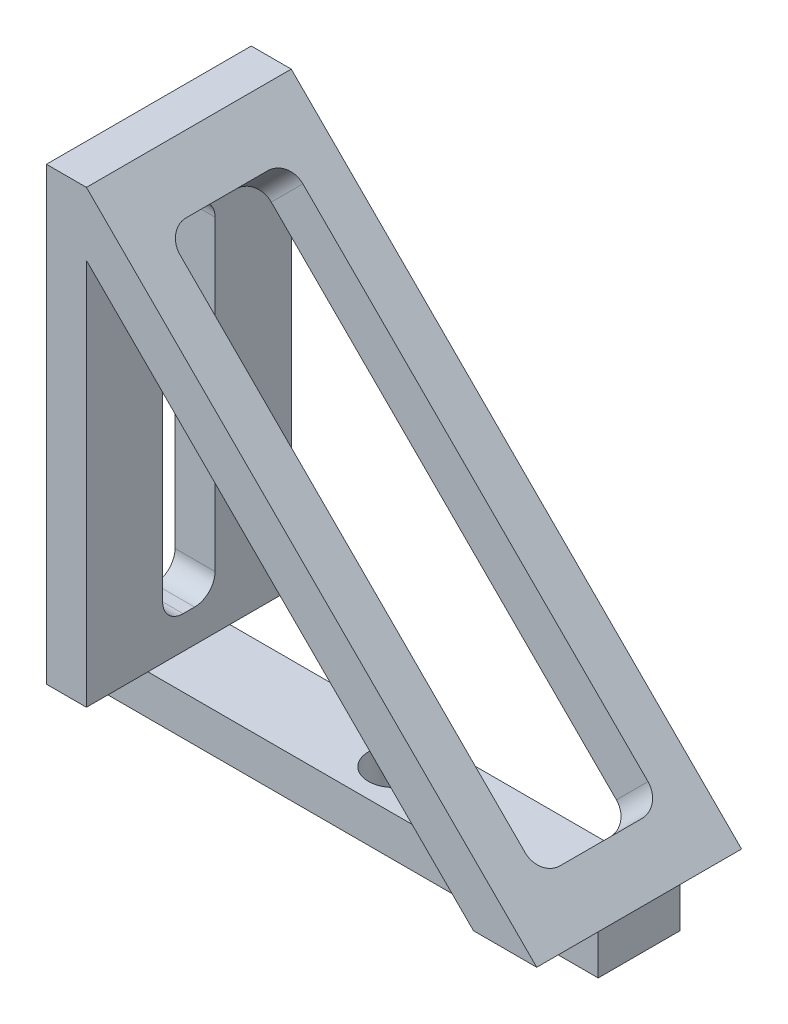
SolidWorks part; units mm, degrees
ref_plane "Front" through (0, 0, 0) normal (0, 0, 1) x (1, 0, 0)
ref_plane "Top" through (0, 0, 0) normal (0, 1, 0) x (1, 0, 0)
ref_plane "Right" through (0, 0, 0) normal (1, 0, 0) x (0, 0, -1)
sketch "Sketch1" plane through (0, 0, 0) normal (0, 0, 1) x (1, 0, 0)
  line L3 (-6.2, 69.8) -> (-6.2, -6.2)
  line L4 (-6.2, -6.2) -> (69.8, -6.2)
  line L6 (-6.2, 69.8) -> (0, 69.8)
  line L7 (0, 69.8) -> (69.8, 0)
  line L8 (50, 0) -> (-50, 0) construction
  line L9 (69.8, 0) -> (69.8, -6.2)
  line L10 (0, 60) -> (60, 0)
  line L11 (60, 0) -> (0, 0)
  line L12 (0, 0) -> (0, 60)
  dimension "D1" = 76
  dimension "D2" = 76
  dimension "D3" = 6.2
  dimension "D4" = 6.2
  dimension "D5" = 60
extrude "Boss-Extrude1" add sketch "Sketch1" along normal mid plane 31.75
sketch "Sketch2" plane through (34.9, 34.9, 0) normal (0.7071, 0.7071, 0) x (0, 0, -1)
  line L0 (0, 50) -> (0, -50) construction
  line L1 (-9.525, -41) -> (9.525, -41)
  line L2 (-9.525, -41) -> (-9.525, 41)
  line L3 (-9.525, 41) -> (9.525, 41)
  line L4 (9.525, -41) -> (9.525, 41)
  line L5 (-9.525, -41) -> (9.525, 41) construction
  line L6 (-9.525, 41) -> (9.525, -41) construction
  point P0 (0, 0)
  point P5 (9.525, 0)
  point P9 (0, 41)
  dimension "D1" = 82
  dimension "D2" = 19.05
extrude "Cut-Extrude1" cut sketch "Sketch2" against normal up to next
sketch "Sketch3" plane through (0, 0, 0) normal (1, 0, 0) x (0, 0, -1)
  line L0 (0, 50) -> (0, -50) construction
  line L1 (-4.064, 5.08) -> (4.064, 5.08)
  line L2 (-4.064, 5.08) -> (-4.064, 59)
  line L3 (-4.064, 59) -> (4.064, 59)
  line L4 (4.064, 5.08) -> (4.064, 59)
  line L5 (-4.064, 5.08) -> (4.064, 59) construction
  line L6 (-4.064, 59) -> (4.064, 5.08) construction
  line L7 (-15.875, 0) -> (15.875, 0) construction
  line L8 (-15.875, 60) -> (15.875, 60) construction
  point P0 (0, 32.04)
  point P5 (0, 59)
  dimension "D1" = 8.128
  dimension "D2" = 5.08
  dimension "D3" = 1
extrude "Cut-Extrude2" cut sketch "Sketch3" against normal up to next
sketch "Sketch4" plane through (69.8, 0, 0) normal (1, 0, 0) x (0, 0, -1)
  line L0 (50, 0) -> (-50, 0) construction
  line L1 (-15.875, -6.2) -> (-6.35, -6.2)
  line L2 (-15.875, -6.2) -> (-15.875, 0)
  line L3 (-15.875, 0) -> (-6.35, 0)
  line L4 (-6.35, -6.2) -> (-6.35, 0)
  line L6 (15.875, -6.2) -> (6.35, -6.2)
  line L7 (15.875, -6.2) -> (15.875, 0)
  line L8 (15.875, 0) -> (6.35, 0)
  line L9 (6.35, -6.2) -> (6.35, 0)
  dimension "D1" = 12.7
extrude "Cut-Extrude3" cut sketch "Sketch4" against normal up to next
sketch "Sketch5" plane through (0, -6.2, 0) normal (0, -1, 0) x (1, 0, 0)
  line L0 (50, 0) -> (-50, 0) construction
  line L1 (-6.2, 6.35) -> (69.8, 6.35) construction
  point P0 (31.8, 0)
  point P5 (31.8, 6.35)
hole_wizard "5/16 (0.3125) Diameter Hole1" positions "Sketch6" profile "Sketch8" hole size "5/16" standard "ANSI Inch" end condition through all
sketch "Sketch6" plane through (0, -6.2, 0) normal (0, -1, 0) x (-1, 0, 0)
  point P0 (-31.8, 0)
sketch "Sketch8" plane through (31.8, -6.2, 0) normal (1, 0, 0) x (0, 0, -1)
  line L0 (0, 0) -> (0, 76)
  line L1 (0, 76) -> (3.9687, 76)
  line L2 (3.9687, 76) -> (3.9687, 0)
  line L5 (3.9687, 0) -> (0, 0)
  line L11 (0, -6.35) -> (0, 107.95) construction
  dimension "Thru Hole Dia." = 7.9375
  dimension "Thru Hole Depth" = 76
fillet "Fillet1" radius 3.175 4 edges at (61.4414, 3.4586, 9.525) (61.4414, 3.4586, -9.525) (3.4586, 61.4414, -9.525) (3.4586, 61.4414, 9.525)
fillet "Fillet2" radius 3.175 4 edges at (-3.1, 5.08, 4.064) (-3.1, 5.08, -4.064) (-3.1, 59, 4.064) (-3.1, 59, -4.064)
